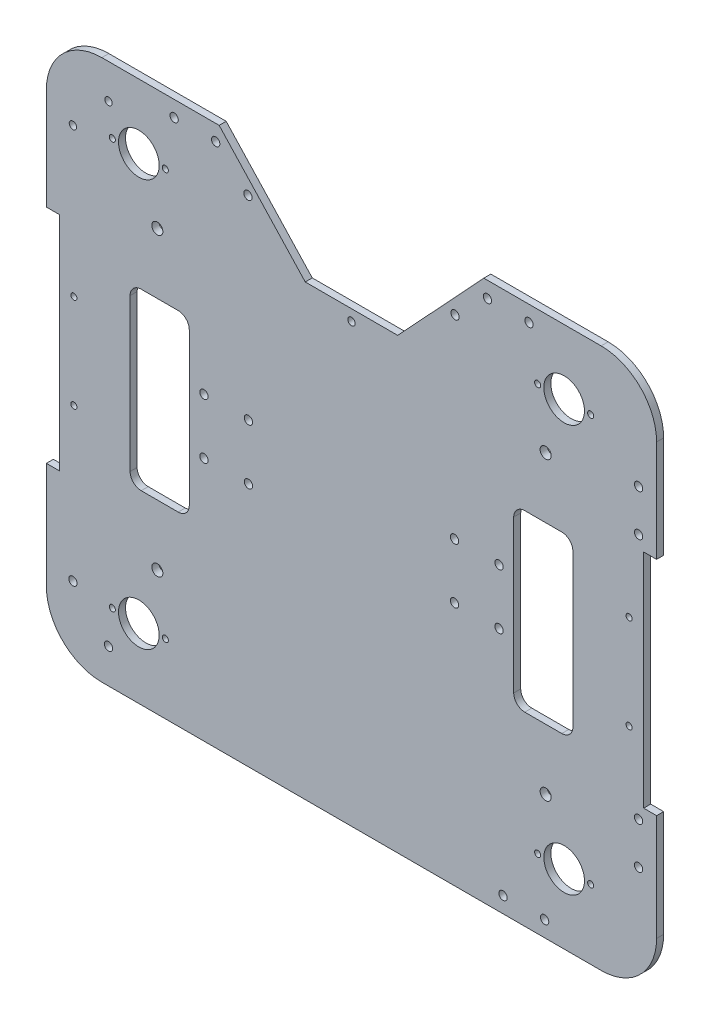
SolidWorks part; units mm, degrees
ref_plane "Front Plane" through (0, 0, 0) normal (0, 0, 1) x (1, 0, 0)
ref_plane "Top Plane" through (0, 0, 0) normal (0, 1, 0) x (1, 0, 0)
ref_plane "Right Plane" through (0, 0, 0) normal (1, 0, 0) x (0, 0, -1)
ref_plane "Plane1" through (0, 150, 0) normal (0, 1, 0) x (1, 0, 0)
ref_plane "Plane2" through (0, -150, 0) normal (0, 1, 0) x (1, 0, 0)
ref_plane "Plane3" through (150, 0, 0) normal (1, 0, 0) x (0, 0, -1)
ref_plane "Plane4" through (-150, 0, 0) normal (1, 0, 0) x (0, 0, -1)
sketch "Sketch2" plane through (0, 0, 0) normal (0, 0, 1) x (1, 0, 0)
  line L0 (0, -10.2) -> (0, 50.0764) construction
  line L1 (-175, 150) -> (175, 150) construction
  line L2 (-175, 150) -> (-175, -150) construction
  line L3 (-175, -150) -> (175, -150) construction
  line L4 (175, 150) -> (175, -150) construction
  line L5 (-175, 150) -> (175, -150) construction
  line L6 (-175, -150) -> (175, 150) construction
  line L7 (165, 115) -> (165, 60)
  line L8 (-135, 145) -> (-71.564, 145)
  line L9 (-71.564, 145) -> (-25.0028, 94.9228)
  line L11 (135, 145) -> (71.564, 145)
  line L12 (-165, 115) -> (-165, 60)
  line L13 (71.564, 145) -> (25.0028, 94.9228)
  line L14 (113.7176, -47.1799) -> (93.7176, -47.1799)
  line L16 (-113.7176, 47.1799) -> (-93.7176, 47.1799)
  line L17 (-119.7176, 41.1799) -> (-119.7176, -41.1799)
  line L18 (-113.7176, -47.1799) -> (-93.7176, -47.1799)
  line L19 (-87.7176, 41.1799) -> (-87.7176, -41.1799)
  line L20 (87.7176, 41.1799) -> (87.7176, -41.1799)
  line L21 (113.7176, 47.1799) -> (93.7176, 47.1799)
  line L22 (119.7176, 41.1799) -> (119.7176, -41.1799)
  line L23 (0, 0) -> (25.5983, 0) construction
  line L24 (100.6652, 110) -> (129.3348, 110) construction
  line L25 (-165, -60) -> (-158, -60)
  line L26 (165, 60) -> (158, 60)
  line L28 (165, -60) -> (158, -60)
  line L29 (158, 60) -> (158, -60)
  line L30 (165, 3.917) -> (158, -60) construction
  line L31 (165.0938, -4.7738) -> (158, 60) construction
  line L32 (-158, 60) -> (-158, -60)
  line L33 (-165, 60) -> (-158, 60)
  line L35 (165, -60) -> (165, -117.5)
  line L36 (-165, -60) -> (-165, -117.5)
  line L37 (-25.0028, 94.9228) -> (25.0028, 94.9228)
  line L38 (-135, -147.5) -> (135, -147.5)
  circle A0 centre (0, 155.625) radius 55 construction
  circle A1 centre (-129.3348, 110) radius 1.65
  circle A2 centre (-100.6652, 110) radius 1.65
  circle A3 centre (129.3348, 110) radius 1.65
  circle A4 centre (100.6652, 110) radius 1.65
  circle A5 centre (129.3348, -110) radius 1.65
  circle A6 centre (100.6652, -110) radius 1.65
  circle A7 centre (-129.3348, -110) radius 1.65
  circle A8 centre (-100.6652, -110) radius 1.65
  circle A9 centre (115, 110) radius 11
  circle A10 centre (-115, 110) radius 11
  circle A11 centre (115, -110) radius 11
  circle A12 centre (-115, -110) radius 11
  circle A13 centre (-105, 80) radius 3
  circle A14 centre (105, 80) radius 3
  circle A15 centre (105, -80) radius 3
  circle A16 centre (-105, -80) radius 3
  circle A17 centre (150.1213, -25.5) radius 1.65
  circle A18 centre (150.1213, 25.5) radius 1.65
  circle A19 centre (-150.1213, -25.5) radius 1.65
  circle A20 centre (-150.1213, 25.5) radius 1.65
  arc A21 (-165, -117.5) -> (-135, -147.5) centre (-135, -117.5) ccw
  arc A26 (165, -117.5) -> (135, -147.5) centre (135, -117.5) cw
  circle A27 centre (-55.73, -14.995) radius 2.25
  circle A32 centre (-55.73, 14.895) radius 2.25
  circle A33 centre (-79.79, 14.895) radius 2.25
  circle A34 centre (-79.79, -14.995) radius 2.25
  circle A35 centre (79.79, -14.995) radius 2.25
  circle A36 centre (55.73, -14.995) radius 2.25
  circle A37 centre (55.73, 14.895) radius 2.25
  circle A38 centre (79.79, 14.895) radius 2.25
  arc A39 (165, 115) -> (135, 145) centre (135, 115) ccw
  arc A40 (-165, 115) -> (-135, 145) centre (-135, 115) cw
  circle A41 centre (56, 120) radius 2.25
  circle A42 centre (0, 88.9228) radius 2
  circle A43 centre (-56, 120) radius 2.25
  arc A44 (-93.7176, -47.1799) -> (-87.7176, -41.1799) centre (-93.7176, -41.1799) ccw
  arc A45 (-119.7176, -41.1799) -> (-113.7176, -47.1799) centre (-113.7176, -41.1799) ccw
  arc A46 (-93.7176, 47.1799) -> (-87.7176, 41.1799) centre (-93.7176, 41.1799) cw
  arc A47 (-113.7176, 47.1799) -> (-119.7176, 41.1799) centre (-113.7176, 41.1799) ccw
  arc A48 (113.7176, -47.1799) -> (119.7176, -41.1799) centre (113.7176, -41.1799) ccw
  arc A49 (93.7176, -47.1799) -> (87.7176, -41.1799) centre (93.7176, -41.1799) cw
  arc A50 (113.7176, 47.1799) -> (119.7176, 41.1799) centre (113.7176, 41.1799) cw
  arc A51 (87.7176, 41.1799) -> (93.7176, 47.1799) centre (93.7176, 41.1799) cw
  circle A55 centre (155.25, 66.7773) radius 2.25
  circle A56 centre (155.25, 89.2566) radius 2.25
  circle A57 centre (155.25, -66.5724) radius 2.25
  circle A58 centre (155.25, -89.0516) radius 2.25
  circle A59 centre (104.4276, -138.95) radius 2.25
  circle A60 centre (81.9484, -138.95) radius 2.25
  circle A61 centre (-131.4003, -128.8803) radius 2.25
  circle A62 centre (-150.6383, -107.9611) radius 2.25
  circle A63 centre (-150.6383, 105.4611) radius 2
  circle A64 centre (-131.4003, 126.3803) radius 2
  circle A65 centre (-73.4375, 136.45) radius 2.25
  circle A66 centre (-95.9167, 136.45) radius 2.25
  circle A67 centre (95.9916, 136.45) radius 2.25
  circle A68 centre (73.5123, 136.45) radius 2.25
  point P0 (0, 0)
  point P17 (0, -147.5)
  point P22 (-87.7176, 0)
  point P25 (0, 94.9228)
  point P59 (164.571, 0)
  point P82 (-165, -147.5)
  point P103 (165, -147.5)
  point P106 (165, 145)
  point P109 (-165, 145)
  point P131 (-87.7176, -47.1799)
  point P137 (-119.7176, -47.1799)
  point P154 (-87.7176, 47.1799)
  point P157 (-119.7176, 47.1799)
  point P160 (119.7176, -47.1799)
  point P163 (87.7176, -47.1799)
  point P166 (119.7176, 47.1799)
  point P169 (87.7176, 47.1799)
  dimension "D3" = 110
  dimension "D8" = 3.3
  dimension "D9" = 3.3
  dimension "D10" = 22
  dimension "D11" = 6
  dimension "D12" = 60
  dimension "D13" = 65
  dimension "D16" = 51
  dimension "D17" = 7.8787
  dimension "D18" = 3.3
  dimension "D19" = 3.3
  dimension "D6" = 14.3348
  dimension "D20" = 14.3348
  dimension "D21" = 50
  dimension "D23" = 4.5
  dimension "D24" = 4.5
  dimension "D25" = 4.5
  dimension "D26" = 4.5
  dimension "D27" = 30
  dimension "D29" = 4.5
  dimension "D31" = 56
  dimension "D32" = 4
  dimension "D33" = 6
  dimension "D34" = 4.5
  dimension "D35" = 4.5
  dimension "D36" = 4.5
  dimension "D37" = 4.5
  dimension "D38" = 4.5
  dimension "D39" = 4.5
  dimension "D40" = 4.5
  dimension "D41" = 4.5
  dimension "D42" = 4.5
  dimension "D43" = 4.5
  dimension "D44" = 4.5
  dimension "D45" = 4.5
  dimension "D46" = 6
  dimension "D47" = 6
  dimension "D1" = 300
  dimension "D2" = 350
  dimension "D4" = 5
  dimension "D5" = 10
  dimension "D14" = 7
  dimension "D15" = 60
  dimension "D22" = 32
  dimension "D28" = 35
  dimension "D30" = 25
extrude "Boss-Extrude1" add sketch "Sketch2" along normal blind 3.8 contours L12 L38 L7 L11 L13 L37 L9 L8 L16 L19 L18 L17 L21 L22 L14 L20
